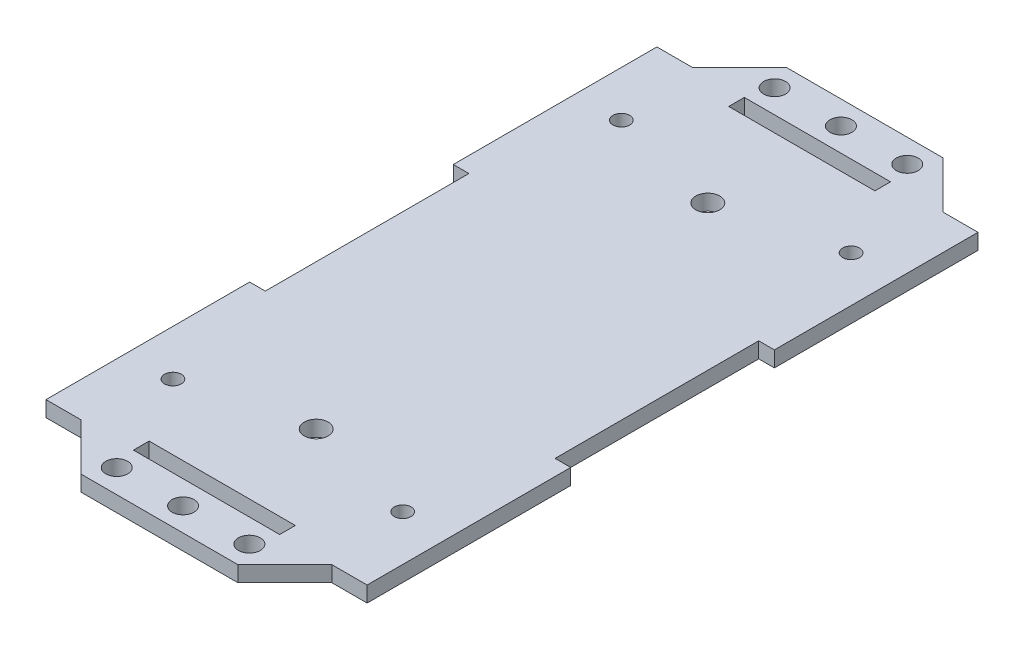
SolidWorks part; units mm, degrees
ref_plane "Front Plane" through (0, 0, 0) normal (0, 0, 1) x (1, 0, 0)
ref_plane "Top Plane" through (0, 0, 0) normal (0, 1, 0) x (1, 0, 0)
ref_plane "Right Plane" through (0, 0, 0) normal (1, 0, 0) x (0, 0, -1)
sketch "Sketch1" plane through (0, 0, 0) normal (0, 1, 0) x (1, 0, 0)
  line L0 (-30.75, 58.5) -> (-30.75, 19.5)
  line L1 (-30.75, -58.5) -> (30.75, -58.5) construction
  line L2 (-30.75, -58.5) -> (-30.75, 58.5) construction
  line L3 (-30.75, 58.5) -> (30.75, 58.5) construction
  line L4 (30.75, -58.5) -> (30.75, 58.5) construction
  line L5 (-30.75, -58.5) -> (30.75, 58.5) construction
  line L6 (-30.75, 58.5) -> (30.75, -58.5) construction
  line L7 (-27.75, -55.5) -> (27.75, -55.5) construction
  line L8 (-27.75, -55.5) -> (-27.75, 55.5) construction
  line L9 (-27.75, 55.5) -> (27.75, 55.5) construction
  line L10 (27.75, -55.5) -> (27.75, 55.5) construction
  line L11 (-27.75, -55.5) -> (27.75, 55.5) construction
  line L12 (-27.75, 55.5) -> (27.75, -55.5) construction
  line L13 (-30.75, 19.5) -> (-27.75, 19.5)
  line L14 (-27.75, 19.5) -> (-27.75, -19.5)
  line L15 (-27.75, -19.5) -> (-30.75, -19.5)
  line L16 (-30.75, -19.5) -> (-30.75, -58.5)
  line L17 (-30.75, -58.5) -> (-14, -58.5)
  line L18 (-14, -58.5) -> (-14, -55.5)
  line L19 (-14, -55.5) -> (14, -55.5)
  line L20 (14, -55.5) -> (14, -58.5)
  line L21 (14, -58.5) -> (30.75, -58.5)
  line L22 (30.75, -58.5) -> (30.75, -19.5)
  line L23 (30.75, -19.5) -> (27.75, -19.5)
  line L24 (27.75, -19.5) -> (27.75, 19.5)
  line L25 (27.75, 19.5) -> (30.75, 19.5)
  line L26 (30.75, 19.5) -> (30.75, 58.5)
  line L27 (30.75, 58.5) -> (14, 58.5)
  line L28 (14, 58.5) -> (14, 55.5)
  line L29 (14, 55.5) -> (-14, 55.5)
  line L30 (-14, 55.5) -> (-14, 58.5)
  line L31 (-14, 58.5) -> (-30.75, 58.5)
  line L32 (0, -37.5) -> (0, 37.5) construction
  line L33 (-22, 42.94) -> (22, 42.94) construction
  line L34 (22, 42.94) -> (22, -42.94) construction
  circle A0 centre (0, 37.5) radius 2.3
  circle A1 centre (0, -37.5) radius 2.3
  circle A2 centre (-22, -42.94) radius 1.6092
  circle A3 centre (22, -42.94) radius 1.6092
  circle A4 centre (22, 42.94) radius 1.6092
  circle A5 centre (-22, 42.94) radius 1.6092
  point P0 (0, 0)
  point P6 (0, 0)
  point P31 (0, 0)
  point P40 (22, 0)
  point P41 (0, 42.94)
  dimension "D6" = 4.6
  dimension "D1" = 61.5
  dimension "D2" = 117
  dimension "D3" = 3
  dimension "D4" = 3
  dimension "D5" = 75
  dimension "D7" = 44
  dimension "D8" = 85.88
  dimension "D9" = 28
extrude "Boss-Extrude1" add sketch "Sketch1" along normal blind 3
sketch "Sketch2" plane through (0, 3, 0) normal (0, 1, 0) x (1, 0, 0)
  line L0 (-24, 58.5) -> (-15, 67.5)
  line L1 (-14, 58.5) -> (-30.75, 58.5) construction
  line L2 (-15, 67.5) -> (15, 67.5)
  line L3 (15, 67.5) -> (24, 58.5)
  line L4 (30.75, 58.5) -> (14, 58.5) construction
  line L5 (24, 58.5) -> (-24, 58.5)
  line L6 (0, 58.5) -> (0, 67.5) construction
  line L7 (-12.7, 63) -> (12.7, 63) construction
  circle A0 centre (0, 63) radius 2.1
  circle A1 centre (12.7, 63) radius 2.1
  circle A2 centre (-12.7, 63) radius 2.1
  point P13 (0, 63)
  point P16 (0, 67.5)
  point P18 (9.9312, 63)
  point P19 (0, 63)
  dimension "D1" = 4.2
  dimension "D2" = 45
  dimension "D3" = 9
  dimension "D4" = 30
  dimension "D5" = 25.4
extrude "Boss-Extrude2" add sketch "Sketch2" against normal blind 3
mirror "Mirror1" about plane through (0, 0, 0) normal (0, 0, 1) of "Boss-Extrude2"
